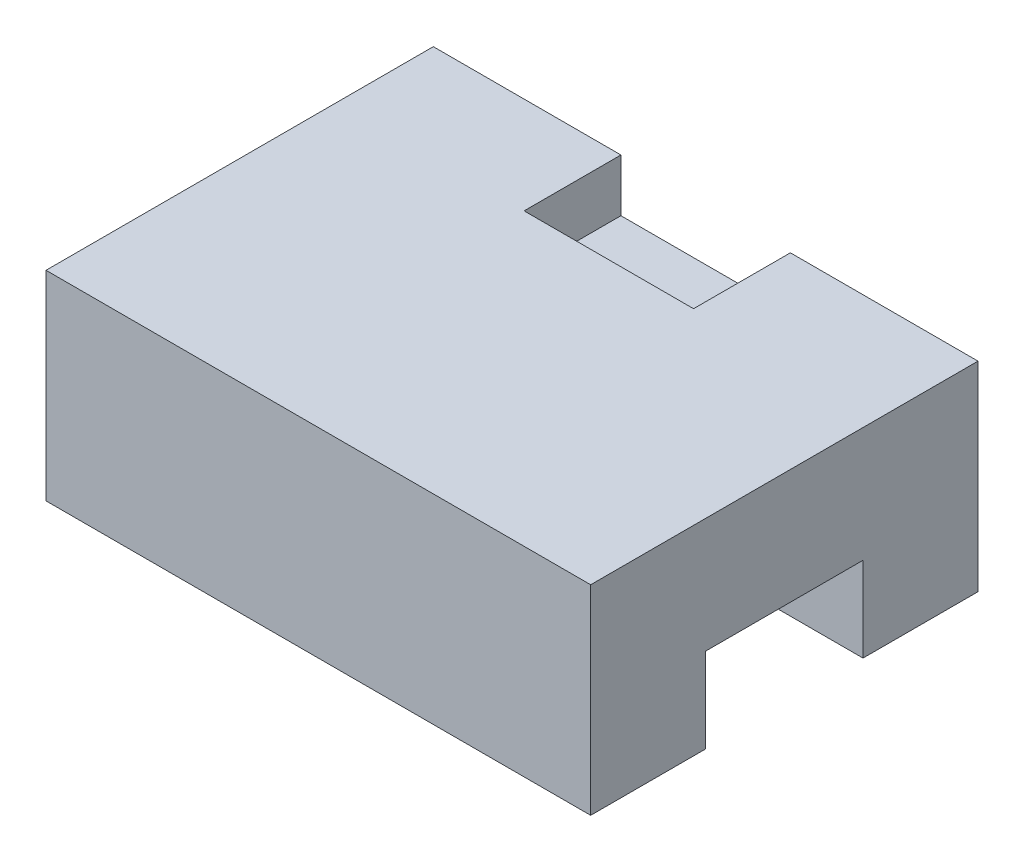
SolidWorks part; units mm, degrees
ref_plane "Front Plane" through (0, 0, 0) normal (0, 0, 1) x (1, 0, 0)
ref_plane "Top Plane" through (0, 0, 0) normal (0, 1, 0) x (1, 0, 0)
ref_plane "Right Plane" through (0, 0, 0) normal (1, 0, 0) x (0, 0, -1)
sketch "Sketch1" plane through (0, 0, 0) normal (0, 0, 1) x (1, 0, 0)
  line L1 (-64.35, 16.8536) -> (25.65, 16.8536)
  line L2 (-64.35, 16.8536) -> (-64.35, -16.1464)
  line L3 (-64.35, -16.1464) -> (25.65, -16.1464)
  line L4 (25.65, 16.8536) -> (25.65, -16.1464)
  dimension "D1" = 33
  dimension "D2" = 90
extrude "Boss-Extrude1" add sketch "Sketch1" against normal blind 64
sketch "Sketch2" plane through (25.65, 0, 0) normal (1, 0, 0) x (0, 0, -1)
  line L0 (19, -16.1464) -> (19, -2.1464)
  line L1 (64, -16.1464) -> (0, -16.1464) construction
  line L2 (19, -2.1464) -> (45, -2.1464)
  line L3 (45, -2.1464) -> (45, -16.1464)
  line L4 (0, -16.1464) -> (0, 16.8536) construction
  line L6 (19, -16.1464) -> (45, -16.1464)
  dimension "D1" = 14
  dimension "D2" = 26
  dimension "D3" = 19
extrude "Cut-Extrude3" cut sketch "Sketch2" against normal up to next
sketch "Sketch3" plane through (0, 0, -64) normal (0, 0, -1) x (-1, 0, 0)
  line L0 (5.35, 16.8536) -> (5.35, 8.1609)
  line L1 (-25.65, 16.8536) -> (64.35, 16.8536) construction
  line L2 (5.35, 8.1609) -> (33.35, 8.1609)
  line L3 (33.35, 8.1609) -> (33.35, 16.8536)
  line L4 (33.35, 16.8536) -> (5.35, 16.8536)
  line L5 (-25.65, -16.1464) -> (-25.65, 16.8536) construction
  dimension "D1" = 28
  dimension "D2" = 31
extrude "Cut-Extrude4" cut sketch "Sketch3" against normal blind 16
